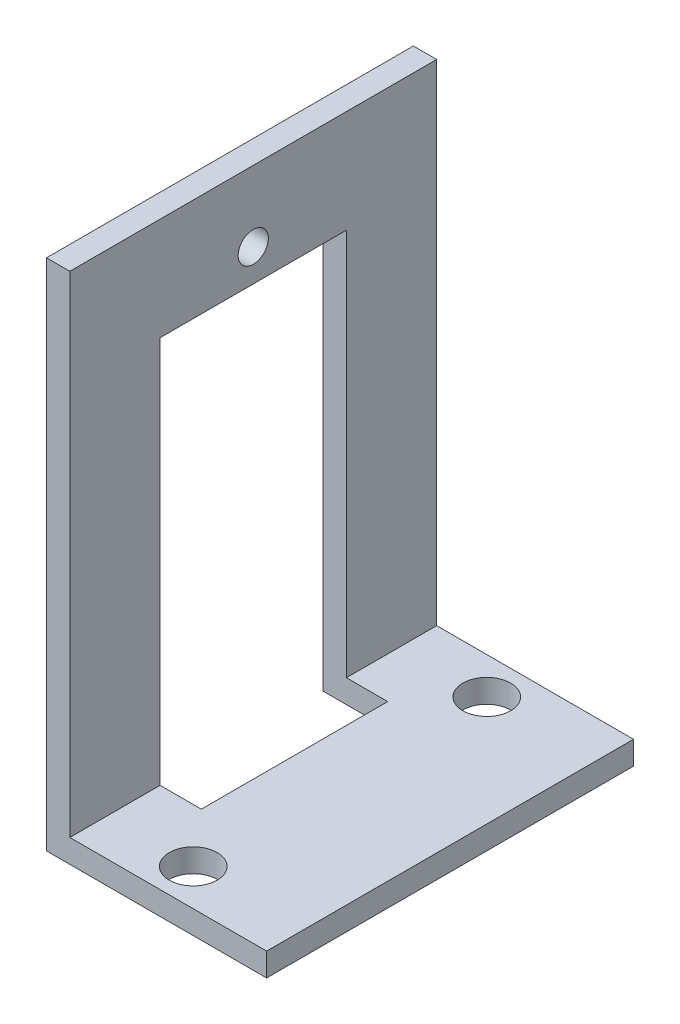
SolidWorks part; units mm, degrees
ref_plane "Front Plane" through (0, 0, 0) normal (0, 0, 1) x (1, 0, 0)
ref_plane "Top Plane" through (0, 0, 0) normal (0, 1, 0) x (1, 0, 0)
ref_plane "Right Plane" through (0, 0, 0) normal (1, 0, 0) x (0, 0, -1)
sketch "Sketch1" plane through (0, 0, 0) normal (0, 0, 1) x (1, 0, 0)
  line L0 (15, 0) -> (0, 0)
  line L1 (0, 0) -> (0, 35)
  line L2 (15, 1.5875) -> (1.5875, 1.5875)
  line L3 (1.5875, 1.5875) -> (1.5875, 35)
  line L4 (0, 35) -> (1.5875, 35)
  line L5 (15, 1.5875) -> (15, 0)
  dimension "D1" = 35
  dimension "D2" = 15
  dimension "D3" = 1.5875
extrude "Boss-Extrude1" add sketch "Sketch1" along normal mid plane 25
hole_wizard "#4 Clearance Hole1" positions "Sketch3" profile "Sketch4" hole size "#4" standard "ANSI Inch"
sketch "Sketch3" plane through (0, 0, 0) normal (0, -1, 0) x (-1, 0, 0)
  line L0 (0, 12.5) -> (-15, 12.5) construction
  line L1 (-15, -12.5) -> (-15, 12.5) construction
  line L2 (0, 0) -> (-15, 0) construction
  point P2 (-7.5, 10)
  point P22 (-7.5, -10)
  dimension "D1" = 2.5
  dimension "D2" = 7.5
sketch "Sketch4" plane through (7.5, 0, -10) normal (1, 0, 0) x (0, 0, -1)
  line L0 (0, 0) -> (0, 2.5671)
  line L1 (0, 2.5671) -> (1.6319, 1.5865)
  line L2 (1.6319, 1.5865) -> (1.6319, 0)
  line L5 (1.6319, 0) -> (0, 0)
  line L10 (0, 2.5671) -> (-1.632, 1.5865) construction
  line L11 (0, -6.35) -> (0, 107.95) construction
  dimension "Hole Dia." = 3.2639
  dimension "Hole Depth" = 1.5865
  dimension "Drill Angle" = 118
hole_wizard "#1 Clearance Hole1" positions "Sketch6" profile "Sketch5" hole size "#1" standard "ANSI Inch"
sketch "Sketch6" plane through (0, 0, 0) normal (-1, 0, 0) x (0, 0, 1)
  line L0 (0, 0) -> (0, 35) construction
  line L1 (12.5, 35) -> (-12.5, 35) construction
  line L3 (12.5, 0) -> (-12.5, 0) construction
  point P0 (0, 30.19)
  dimension "D1" = 30.19
sketch "Sketch5" plane through (0, 30.19, 0) normal (0, 1, 0) x (0, 0, 1)
  line L0 (0, 0) -> (0, 2.2046)
  line L1 (0, 2.2046) -> (1.0287, 1.5865)
  line L2 (1.0287, 1.5865) -> (1.0287, 0)
  line L5 (1.0287, 0) -> (0, 0)
  line L10 (0, 2.2046) -> (-1.0287, 1.5865) construction
  line L11 (0, -6.35) -> (0, 107.95) construction
  dimension "Hole Dia." = 2.0574
  dimension "Hole Depth" = 1.5865
  dimension "Drill Angle" = 118
sketch "Sketch7" plane through (0, 0, 0) normal (-1, 0, 0) x (0, 0, 1)
  line L0 (12.5, 0) -> (-12.5, 0) construction
  line L1 (-6.35, 0) -> (6.35, 0)
  line L2 (-6.35, 0) -> (-6.35, 28)
  line L3 (-6.35, 28) -> (6.35, 28)
  line L4 (6.35, 0) -> (6.35, 28)
  dimension "D1" = 12.7
  dimension "D2" = 28
extrude "Cut-Extrude1" cut sketch "Sketch7" against normal blind 4.4
